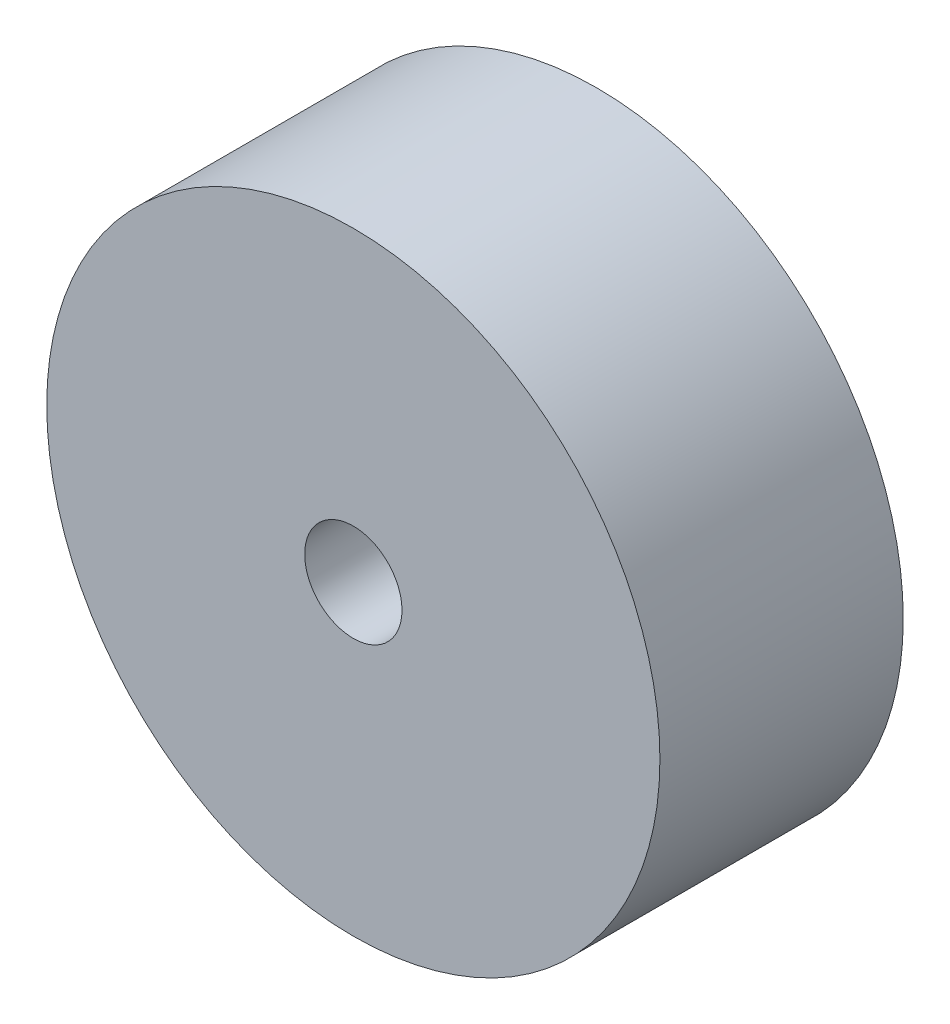
SolidWorks part; units mm, degrees
ref_plane "Спереди" through (0, 0, 0) normal (0, 0, 1) x (1, 0, 0)
ref_plane "Сверху" through (0, 0, 0) normal (0, 1, 0) x (1, 0, 0)
ref_plane "Справа" through (0, 0, 0) normal (1, 0, 0) x (0, 0, -1)
sketch "Эскиз1" plane through (0, 0, 0) normal (0, 0, 1) x (1, 0, 0)
  circle A0 centre (0, 0) radius 31.5
  circle A1 centre (0, 0) radius 5
  dimension "D1" = 63
  dimension "D2" = 10
extrude "Вытянуть1" add sketch "Эскиз1" along normal blind 25
